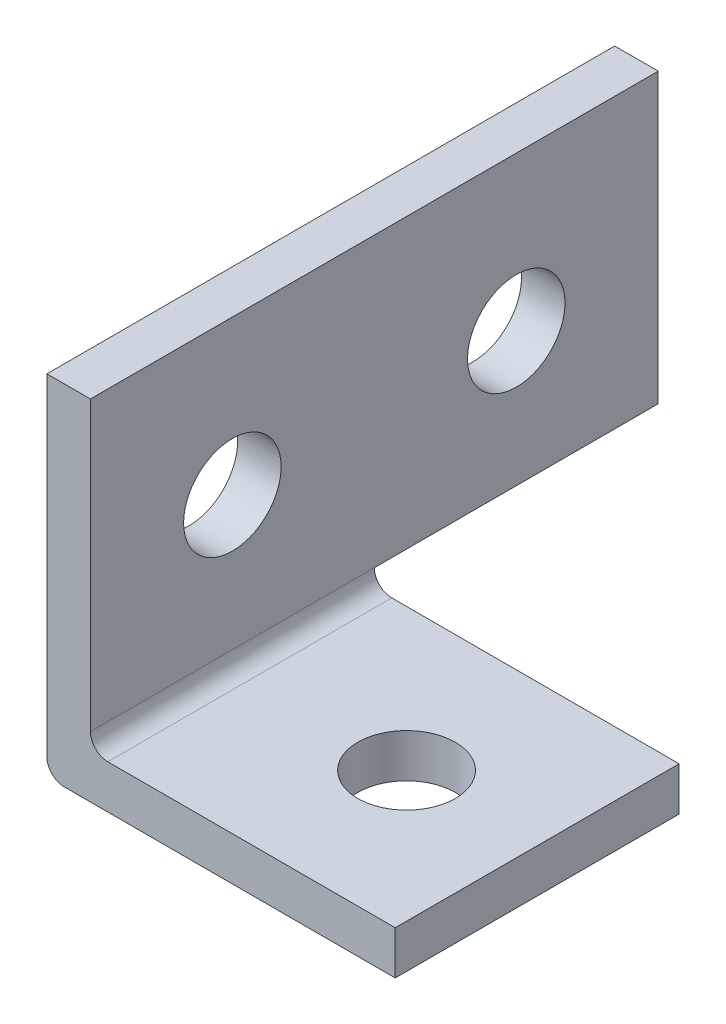
SolidWorks part; units mm, degrees
ref_plane "前视基准面" through (0, 0, 0) normal (0, 0, 1) x (1, 0, 0)
ref_plane "上视基准面" through (0, 0, 0) normal (0, 1, 0) x (1, 0, 0)
ref_plane "右视基准面" through (0, 0, 0) normal (1, 0, 0) x (0, 0, -1)
sketch "草图1" plane through (0, 0, 0) normal (0, 0, 1) x (1, 0, 0)
  line L0 (2.54, 0) -> (50.8, 0)
  line L1 (50.8, 0) -> (50.8, 6.35)
  line L2 (50.8, 6.35) -> (8.89, 6.35)
  line L3 (0, 2.54) -> (0, 50.901)
  line L4 (0, 50.901) -> (6.35, 50.901)
  line L5 (6.35, 50.901) -> (6.35, 8.89)
  arc A0 (6.35, 8.89) -> (8.89, 6.35) centre (8.89, 8.89) ccw
  arc A1 (0, 2.54) -> (2.54, 0) centre (2.54, 2.54) ccw
  point P11 (0, 0)
  dimension "D1" = 2.54
  dimension "D2" = 2.54
extrude "凸台-拉伸1" add sketch "草图1" along normal blind 41.402
ref_plane "基准面1" through (0, 0, 0) normal (0, -1, 0) x (-1, 0, 0)
sketch "草图3" plane through (0, 0, 0) normal (0, -1, 0) x (-1, 0, 0)
  line L0 (0, -20.701) -> (-31.75, -20.701) construction
  line L1 (0, -41.402) -> (0, 0) construction
  circle A0 centre (-31.75, -20.701) radius 7.112
ref_plane "基准面2" through (0, 0, 0) normal (-1, 0, 0) x (0, 0, 1)
sketch "草图4" plane through (0, 0, 0) normal (-1, 0, 0) x (0, 0, 1)
  line L0 (20.701, 0) -> (20.701, 28.448) construction
  line L1 (13.589, 0) -> (27.813, 0) construction
  circle A0 centre (20.701, 28.448) radius 7.112
extrude "切除-拉伸1" cut sketch "草图4" against normal through all
extrude "切除-拉伸2" cut sketch "草图3" against normal through all contours A0
ref_plane "Plane1" through (6.35, 0, 0) normal (1, 0, 0) x (0, 0, -1)
sketch "Sketch1" plane through (6.35, 0, 0) normal (1, 0, 0) x (0, 0, -1)
  line L0 (0, 50.901) -> (41.402, 50.901)
  line L1 (41.402, 50.901) -> (41.402, 8.89)
  line L2 (41.402, 8.89) -> (0, 8.89)
  line L3 (0, 8.89) -> (0, 50.901)
extrude "Boss-Extrude1" add sketch "Sketch1" against normal blind 6.35
sketch "Sketch2" plane through (6.35, 0, 0) normal (1, 0, 0) x (0, 0, -1)
  line L0 (0, 8.89) -> (0, 50.901) construction
  line L1 (-41.402, 50.901) -> (41.402, 50.901) construction
  circle A0 centre (-20.701, 28.448) radius 7.112
  circle A1 centre (20.701, 28.448) radius 7.112
extrude "Cut-Extrude1" cut sketch "Sketch2" against normal through all
